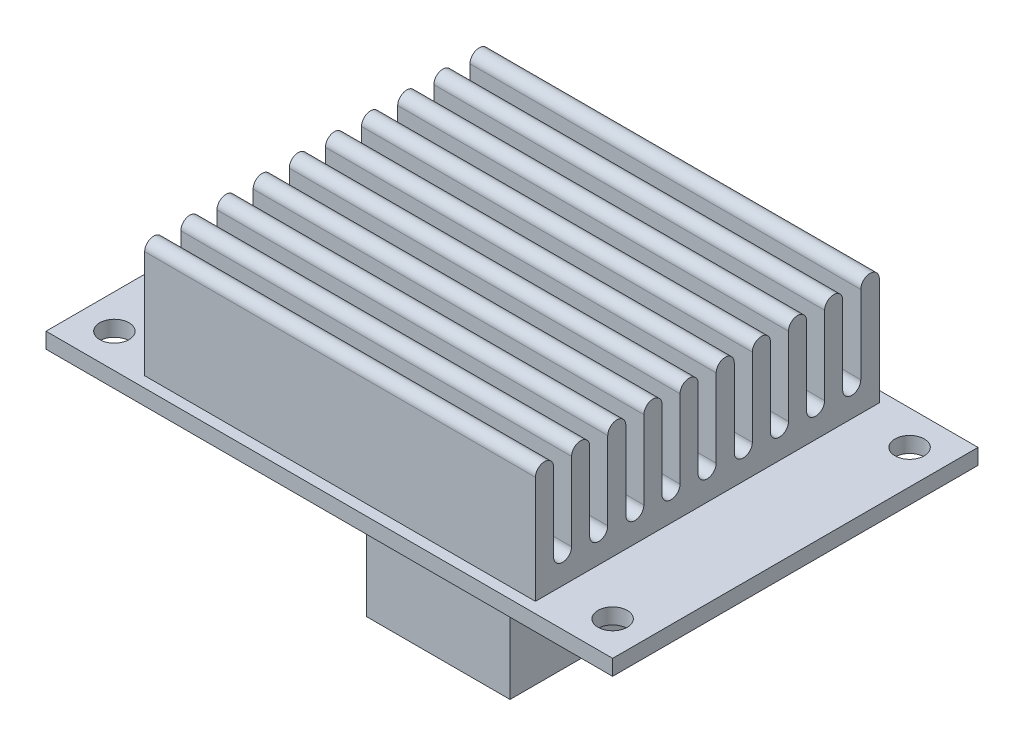
SolidWorks part; units mm, degrees
ref_plane "Front Plane" through (0, 0, 0) normal (0, 0, 1) x (1, 0, 0)
ref_plane "Top Plane" through (0, 0, 0) normal (0, 1, 0) x (1, 0, 0)
ref_plane "Right Plane" through (0, 0, 0) normal (1, 0, 0) x (0, 0, -1)
sketch "Sketch1" plane through (0, 0, 0) normal (0, 1, 0) x (1, 0, 0)
  line L0 (-25.5, 15.2) -> (25.5, 15.2) construction
  line L1 (-29, -18.7) -> (29, -18.7)
  line L2 (-29, -18.7) -> (-29, 18.7)
  line L3 (-29, 18.7) -> (29, 18.7)
  line L4 (29, -18.7) -> (29, 18.7)
  line L5 (-29, -18.7) -> (29, 18.7) construction
  line L6 (-29, 18.7) -> (29, -18.7) construction
  line L7 (25.5, -15.2) -> (25.5, 15.2) construction
  line L8 (-25.5, -15.2) -> (25.5, -15.2) construction
  line L9 (-25.5, -15.2) -> (-25.5, 15.2) construction
  circle A0 centre (25.5, 15.2) radius 1.5
  circle A1 centre (25.5, -15.2) radius 1.5
  circle A2 centre (-25.5, -15.2) radius 1.5
  circle A3 centre (-25.5, 15.2) radius 1.5
  point P0 (0, 0)
  dimension "D4" = 3
  dimension "D5" = 3
  dimension "D6" = 3
  dimension "D7" = 3
  dimension "D1" = 37.4
  dimension "D2" = 58
  dimension "D3" = 3.5
extrude "Boss-Extrude1" add sketch "Sketch1" along normal blind 1.6
sketch "Sketch2" plane through (0, 0, 0) normal (1, 0, 0) x (0, 0, -1)
  line L0 (-18.7, 1.6) -> (18.7, 1.6) construction
  line L1 (-17.6, 1.6) -> (18.7, 1.6)
  line L2 (-17.6, 1.6) -> (-17.6, 12.6)
  line L3 (-15.75, 12.6) -> (-15.75, 4.6)
  line L4 (-13.9, 4.6) -> (-13.9, 12.6)
  line L5 (17.6, 1.6) -> (17.6, 12.6)
  line L6 (-12.05, 12.6) -> (-12.05, 4.6)
  line L7 (-10.2, 4.6) -> (-10.2, 12.6)
  line L8 (-8.35, 12.6) -> (-8.35, 4.6)
  line L9 (-6.5, 4.6) -> (-6.5, 12.6)
  line L10 (-4.65, 12.6) -> (-4.65, 4.6)
  line L11 (-2.8, 4.6) -> (-2.8, 12.6)
  line L12 (-0.95, 12.6) -> (-0.95, 4.6)
  line L13 (0.9, 4.6) -> (0.9, 12.6)
  line L14 (2.75, 12.6) -> (2.75, 4.6)
  line L15 (4.6, 4.6) -> (4.6, 12.6)
  line L16 (6.45, 12.6) -> (6.45, 4.6)
  line L17 (8.3, 4.6) -> (8.3, 12.6)
  line L18 (10.15, 12.6) -> (10.15, 4.6)
  line L19 (12, 4.6) -> (12, 12.6)
  line L20 (13.85, 12.6) -> (13.85, 4.6)
  line L21 (15.7, 4.6) -> (15.7, 12.6)
  line L22 (-15.75, 12.6) -> (-12.05, 12.6) construction
  line L23 (18.7, 1.6) -> (18.7, 0) construction
  arc A0 (-17.6, 12.6) -> (-15.75, 12.6) centre (-16.675, 12.6) cw
  arc A1 (-15.75, 4.6) -> (-13.9, 4.6) centre (-14.825, 4.6) ccw
  arc A2 (-13.9, 12.6) -> (-12.05, 12.6) centre (-12.975, 12.6) cw
  arc A3 (-12.05, 4.6) -> (-10.2, 4.6) centre (-11.125, 4.6) ccw
  arc A4 (-10.2, 12.6) -> (-8.35, 12.6) centre (-9.275, 12.6) cw
  arc A5 (-8.35, 4.6) -> (-6.5, 4.6) centre (-7.425, 4.6) ccw
  arc A6 (-6.5, 12.6) -> (-4.65, 12.6) centre (-5.575, 12.6) cw
  arc A7 (-4.65, 4.6) -> (-2.8, 4.6) centre (-3.725, 4.6) ccw
  arc A8 (-2.8, 12.6) -> (-0.95, 12.6) centre (-1.875, 12.6) cw
  arc A9 (-0.95, 4.6) -> (0.9, 4.6) centre (-0.025, 4.6) ccw
  arc A10 (0.9, 12.6) -> (2.75, 12.6) centre (1.825, 12.6) cw
  arc A11 (2.75, 4.6) -> (4.6, 4.6) centre (3.675, 4.6) ccw
  arc A12 (4.6, 12.6) -> (6.45, 12.6) centre (5.525, 12.6) cw
  arc A13 (6.45, 4.6) -> (8.3, 4.6) centre (7.375, 4.6) ccw
  arc A14 (8.3, 12.6) -> (10.15, 12.6) centre (9.225, 12.6) cw
  arc A15 (10.15, 4.6) -> (12, 4.6) centre (11.075, 4.6) ccw
  arc A16 (12, 12.6) -> (13.85, 12.6) centre (12.925, 12.6) cw
  arc A17 (13.85, 4.6) -> (15.7, 4.6) centre (14.775, 4.6) ccw
  arc A18 (15.7, 12.6) -> (17.6, 12.6) centre (16.65, 12.6) cw
  dimension "D2" = 0.925
  dimension "D3" = 0.925
  dimension "D1" = 11
  dimension "D4" = 8
  dimension "D5" = 35.2
  dimension "D6" = 3.7
  dimension "D7" = 1.1
  dimension "D8" = 9
extrude "Boss-Extrude2" add sketch "Sketch2" along normal blind 20 and the other way blind 20 separate body contours L22 L4 A1 L3 A0 L2 L1 L5 A18 L21 A17 L20 A16 L19 A15 L18 A14 L17 A13 L16 A12 L15 A11 L14 A10 L13 A9 L12 A8 L11 A7 L10 A6 L9 A5 L8 A4 L7 A3 L6 | A2 L22
sketch "Sketch3" plane through (0, 0, 0) normal (0, -1, 0) x (-1, 0, 0)
  line L0 (-29, -18.7) -> (-29, 18.7) construction
  line L1 (-3.3, -3.9) -> (-18, -3.9)
  line L2 (-3.3, -3.9) -> (-3.3, -18.2)
  line L3 (-3.3, -18.2) -> (-18, -18.2)
  line L4 (-18, -3.9) -> (-18, -18.2)
  line L5 (-3.3, -3.9) -> (-18, -18.2) construction
  line L6 (-3.3, -18.2) -> (-18, -3.9) construction
  line L7 (29, -18.7) -> (-29, -18.7) construction
  point P0 (-10.65, -11.05)
  dimension "D1" = 14.7
  dimension "D2" = 14.3
  dimension "D3" = 11
  dimension "D4" = 0.5
extrude "Boss-Extrude3" add sketch "Sketch3" along normal blind 7.8 separate body
sketch "Sketch4" plane through (0, 0, 0) normal (0, -1, 0) x (-1, 0, 0)
  line L0 (-29, 18.7) -> (29, 18.7) construction
  line L1 (-29, -18.7) -> (-29, 18.7) construction
  line L2 (-7, 14.4) -> (-7, 5.9) construction
  circle A0 centre (-7, 14.4) radius 4
  circle A1 centre (-7, 5.9) radius 4
  dimension "D1" = 8
  dimension "D2" = 8
  dimension "D3" = 4.3
  dimension "D4" = 22
  dimension "D5" = 8.5
extrude "Boss-Extrude4" add sketch "Sketch4" along normal blind 10.7 separate body
sketch "Sketch5" plane through (0, 0, 0) normal (0, -1, 0) x (-1, 0, 0)
  line L0 (-29, 18.7) -> (29, 18.7) construction
  line L1 (28.8, 12.2) -> (19.3, 12.2)
  line L2 (28.8, 12.2) -> (28.8, 2.8)
  line L3 (28.8, 2.8) -> (19.3, 2.8)
  line L4 (19.3, 12.2) -> (19.3, 2.8)
  line L5 (28.8, 12.2) -> (19.3, 2.8) construction
  line L6 (28.8, 2.8) -> (19.3, 12.2) construction
  line L7 (29, 18.7) -> (29, -18.7) construction
  point P0 (24.05, 7.5)
  dimension "D1" = 9.4
  dimension "D2" = 9.5
  dimension "D3" = 6.5
  dimension "D4" = 0.2
extrude "Boss-Extrude5" add sketch "Sketch5" along normal blind 10 separate body
equation "\"D5@Sketch1\"=\"D4@Sketch1\""
equation "\"D6@Sketch1\"=\"D4@Sketch1\""
equation "\"D7@Sketch1\"=\"D4@Sketch1\""
equation "\"D3@Sketch2\"=\"D2@Sketch2\""
